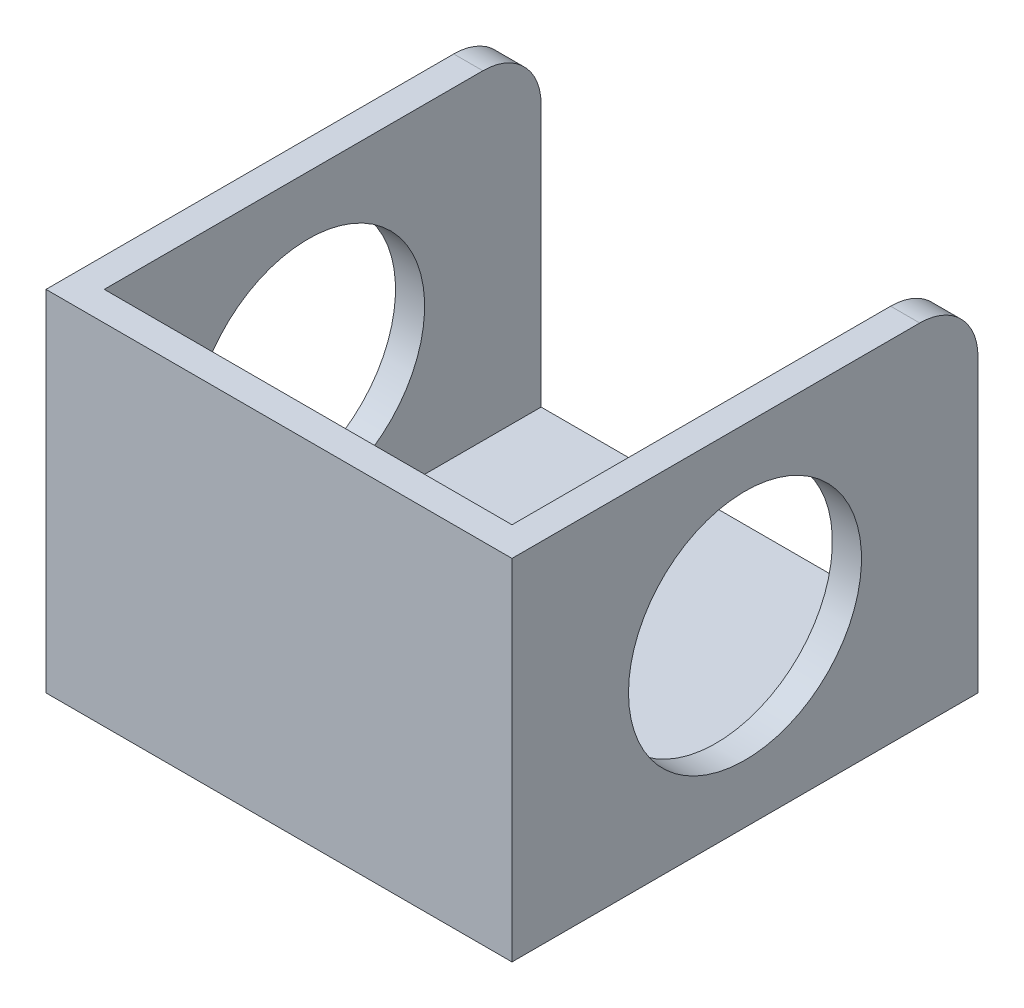
SolidWorks part; units mm, degrees
material "1060 Alloy"
ref_plane "Front Plane" through (0, 0, 0) normal (0, 0, 1) x (1, 0, 0)
ref_plane "Top Plane" through (0, 0, 0) normal (0, 1, 0) x (1, 0, 0)
ref_plane "Right Plane" through (0, 0, 0) normal (1, 0, 0) x (0, 0, -1)
sketch "Sketch1" plane through (0, 0, 0) normal (0, 1, 0) x (1, 0, 0)
  line L1 (-101.6, -101.6) -> (101.6, -101.6)
  line L2 (-101.6, -101.6) -> (-101.6, 101.6)
  line L3 (-101.6, 101.6) -> (101.6, 101.6)
  line L4 (101.6, -101.6) -> (101.6, 101.6)
  line L5 (-101.6, -101.6) -> (101.6, 101.6) construction
  line L6 (-101.6, 101.6) -> (101.6, -101.6) construction
  circle A0 centre (0, 0) radius 101.6
  point P0 (0, 0)
  dimension "D1" = 203.2
extrude "Boss-Extrude1" add sketch "Sketch1" along normal blind 152.4 contours A0 L1 L4 | A0 L4 L3 | A0 L3 L2 | A0 L2 L1 | A0
shell "Shell1" thickness 12.7
sketch "Sketch2" plane through (0, 0, 0) normal (0, -1, 0) x (1, 0, 0)
  circle A0 centre (0, 0) radius 22.86
  dimension "D1" = 45.72
extrude "Boss-Extrude2" add sketch "Sketch2" along normal blind 30.48
sketch "Sketch3" plane through (-101.6, 0, 0) normal (-1, 0, 0) x (0, 0, 1)
  circle A0 centre (0, 76.2) radius 50.8
  dimension "D1" = 101.6
extrude "Cut-Extrude1" cut sketch "Sketch3" against normal through all
fillet "Fillet1" radius 25.4 1 edges at (-95.25, 152.4, -101.6)
fillet "Fillet2" radius 25.4 1 edges at (95.25, 152.4, -101.6)
